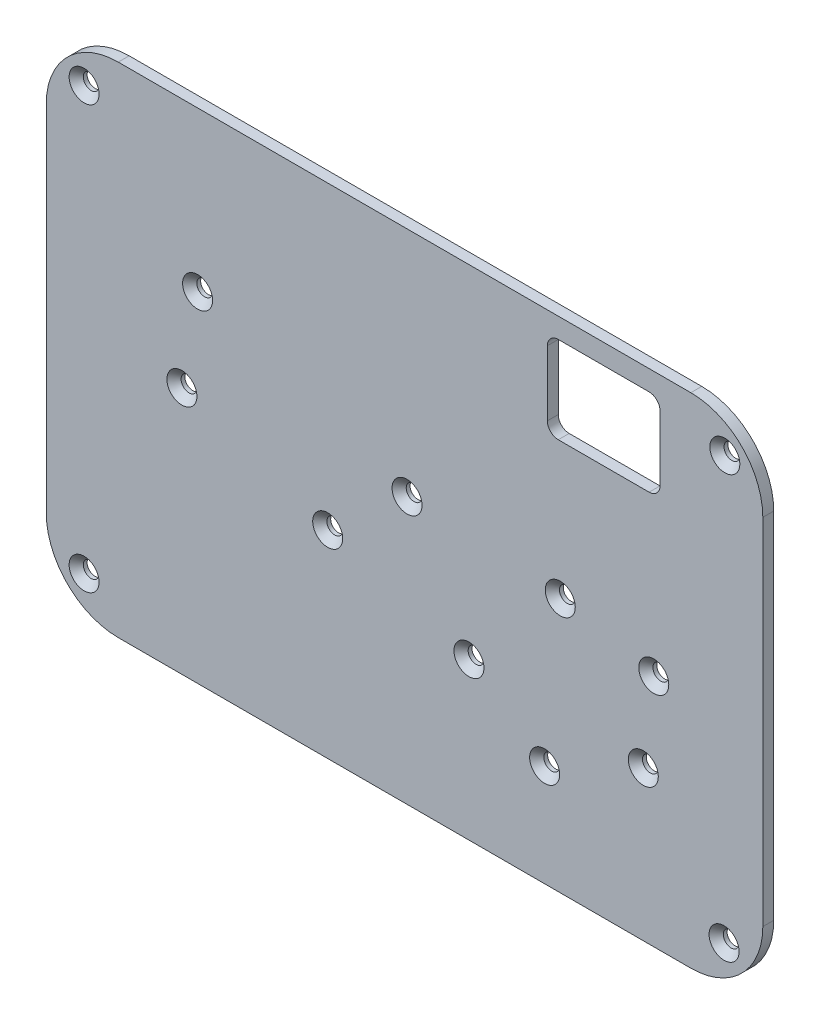
SolidWorks part; units mm, degrees
material "Легированная сталь"
ref_plane "Спереди" through (0, 0, 0) normal (0, 0, 1) x (1, 0, 0)
ref_plane "Сверху" through (0, 0, 0) normal (0, 1, 0) x (1, 0, 0)
ref_plane "Справа" through (0, 0, 0) normal (1, 0, 0) x (0, 0, -1)
sketch "Эскиз9" plane through (0, 0, 0) normal (0, 0, 1) x (1, 0, 0)
  line L0 (89.2786, -11) -> (85.3215, -11)
  line L1 (79.0604, -10) -> (0, -10)
  line L2 (-10, 0) -> (-10, 31.7451)
  line L3 (-11, 38.0208) -> (-11, 41.9792)
  line L4 (-10, 48.1396) -> (-10, 65)
  line L5 (0, 75) -> (12.025, 75)
  line L6 (12.025, 75) -> (12.025, 78.2)
  line L7 (12.025, 78.2) -> (0, 78.2)
  line L8 (-13.2, 65) -> (-13.2, 0)
  line L9 (0, -13.2) -> (105, -13.2)
  line L10 (118.2, 0) -> (118.2, 65)
  line L11 (105, 78.2) -> (30.025, 78.2)
  line L12 (30.025, 78.2) -> (30.025, 75)
  line L13 (30.025, 75) -> (105, 75)
  line L14 (115, 65) -> (115, 0)
  line L15 (105, -10) -> (95.3396, -10)
  circle A0 centre (-6.2627, 71.3457) radius 2.75
  circle A1 centre (-6.2627, -6.1474) radius 2.75
  circle A2 centre (111.0955, -6.1474) radius 2.75
  circle A3 centre (111.2331, 71.3457) radius 2.75
  arc A4 (93.9799, -9.4667) -> (95.3396, -10) centre (95.3396, -8) ccw
  arc A5 (93.9799, -9.4667) -> (92.5665, -9.5204) centre (93.3, -10.2) ccw
  arc A6 (91.5856, -10.1011) -> (92.5665, -9.5204) centre (91.0994, -8.1611) ccw
  arc A7 (91.5856, -10.1011) -> (90.4374, -10.6301) centre (92.4155, -13.4129) ccw
  arc A8 (89.2786, -11) -> (90.4374, -10.6301) centre (89.2786, -9) ccw
  arc A9 (84.1626, -10.63) -> (85.3215, -11) centre (85.3215, -9) ccw
  arc A10 (84.1626, -10.63) -> (82.8537, -10.0647) centre (82.1842, -13.4126) ccw
  arc A11 (81.8153, -9.5012) -> (82.8537, -10.0647) centre (83.2459, -8.1035) ccw
  arc A12 (81.8153, -9.5012) -> (80.4201, -9.4667) centre (81.1, -10.2) ccw
  arc A13 (79.0604, -10) -> (80.4201, -9.4667) centre (79.0604, -8) ccw
  arc A14 (-1.5835, -9.8738) -> (0, -10) centre (0, 0) ccw
  arc A15 (-3.1229, -7.1543) -> (-1.5835, -9.8738) centre (-1.2668, -7.8991) ccw
  arc A16 (-3.1229, -7.1543) -> (-7.1543, -3.1229) centre (-6, -6) ccw
  arc A17 (-9.8738, -1.5835) -> (-7.1543, -3.1229) centre (-7.8991, -1.2668) ccw
  arc A18 (-10, 0) -> (-9.8738, -1.5835) centre (0, 0) ccw
  arc A19 (-9.5149, 33.0509) -> (-10, 31.7451) centre (-8, 31.7451) ccw
  arc A20 (-9.5149, 33.0509) -> (-9.5827, 34.8219) centre (-10.5, 33.9) ccw
  arc A21 (-10.1084, 35.7395) -> (-9.5827, 34.8219) centre (-8.172, 36.2397) ccw
  arc A22 (-10.1084, 35.7395) -> (-10.6306, 36.8627) centre (-13.4142, 34.8858) ccw
  arc A23 (-11, 38.0208) -> (-10.6306, 36.8627) centre (-9, 38.0208) ccw
  arc A24 (-10.6306, 43.1373) -> (-11, 41.9792) centre (-9, 41.9792) ccw
  arc A25 (-10.6306, 43.1373) -> (-10.0831, 44.3655) centre (-13.4142, 45.1142) ccw
  arc A26 (-9.5106, 45.3756) -> (-10.0831, 44.3655) centre (-8.1318, 43.9269) ccw
  arc A27 (-9.5106, 45.3756) -> (-9.4667, 46.7799) centre (-10.2, 46.1) ccw
  arc A28 (-10, 48.1396) -> (-9.4667, 46.7799) centre (-8, 48.1396) ccw
  arc A29 (-9.8738, 66.5835) -> (-10, 65) centre (0, 65) ccw
  arc A30 (-7.1543, 68.1229) -> (-9.8738, 66.5835) centre (-7.8991, 66.2668) ccw
  arc A31 (-7.1543, 68.1229) -> (-3.1229, 72.1543) centre (-6, 71) ccw
  arc A32 (-1.5835, 74.8738) -> (-3.1229, 72.1543) centre (-1.2668, 72.8991) ccw
  arc A33 (0, 75) -> (-1.5835, 74.8738) centre (0, 65) ccw
  arc A34 (0, 78.2) -> (-13.2, 65) centre (0, 65) ccw
  arc A35 (-13.2, 0) -> (0, -13.2) centre (0, 0) ccw
  arc A36 (105, -13.2) -> (118.2, 0) centre (105, 0) ccw
  arc A37 (118.2, 65) -> (105, 78.2) centre (105, 65) ccw
  arc A38 (106.5835, 74.8738) -> (105, 75) centre (105, 65) ccw
  arc A39 (108.1229, 72.1543) -> (106.5835, 74.8738) centre (106.2668, 72.8991) ccw
  arc A40 (108.1229, 72.1543) -> (112.1543, 68.1229) centre (111, 71) ccw
  arc A41 (114.8738, 66.5835) -> (112.1543, 68.1229) centre (112.8991, 66.2668) ccw
  arc A42 (115, 65) -> (114.8738, 66.5835) centre (105, 65) ccw
  arc A43 (114.8738, -1.5835) -> (115, 0) centre (105, 0) ccw
  arc A44 (112.1543, -3.1229) -> (114.8738, -1.5835) centre (112.8991, -1.2668) ccw
  arc A45 (112.1543, -3.1229) -> (108.1229, -7.1543) centre (111, -6) ccw
  arc A46 (106.5835, -9.8738) -> (108.1229, -7.1543) centre (106.2668, -7.8991) ccw
  arc A47 (105, -10) -> (106.5835, -9.8738) centre (105, 0) ccw
sketch "Net" plane through (0, 0, 0) normal (0, 0, 1) x (1, 0, 0)
  line L0 (24.2, 33) -> (24.2, 43.5)
  line L1 (22.2, 45.5) -> (16.7, 45.5)
  line L2 (14.7, 43.5) -> (14.7, 33)
  line L3 (16.7, 31) -> (22.2, 31)
  line L4 (49.7, 24.5) -> (49.7, 35.5)
  line L5 (47.7, 37.5) -> (43.2, 37.5)
  line L6 (41.2, 35.5) -> (41.2, 24.5)
  line L7 (43.2, 22.5) -> (47.7, 22.5)
  line L8 (76.2, 28) -> (67.2, 28)
  line L9 (65.2, 26) -> (65.2, 22)
  line L10 (67.2, 20) -> (76.2, 20)
  line L11 (78.2, 22) -> (78.2, 26)
  line L12 (86.2, 32.5) -> (96.2, 32.5)
  line L13 (98.2, 34.5) -> (98.2, 35.5)
  line L14 (96.2, 37.5) -> (86.2, 37.5)
  line L15 (84.2, 35.5) -> (84.2, 34.5)
  line L16 (78.2, -9) -> (81.2, -9)
  line L17 (78.2, 0.6303) -> (78.2, -9)
  line L18 (78.2, 16) -> (78.2, 10.096)
  line L19 (69.4574, 18) -> (76.2, 18)
  line L20 (67.4574, 14.9) -> (67.4574, 16)
  line L21 (54.8273, 16.5) -> (59.2731, 16.5)
  line L22 (38.1419, 19.7) -> (47.4957, 19.7)
  line L23 (35.0419, 23) -> (35.0419, 22.8)
  line L24 (26.2, 25) -> (33.0419, 25)
  line L25 (11.5609, 29) -> (22.2, 29)
  line L26 (8.4609, 32.5) -> (8.4609, 32.1)
  line L27 (1.4933, 34.5) -> (6.4609, 34.5)
  line L28 (-8.6, 32) -> (-2.8, 32)
  line L29 (-8.6, 34) -> (-8.6, 32)
  line L30 (-2.8, 34) -> (-8.6, 34)
  line L31 (-0.8, 44) -> (-0.8, 36)
  line L32 (-8.6, 46) -> (-2.8, 46)
  line L33 (-8.6, 48) -> (-8.6, 46)
  line L34 (-2.8, 48) -> (-8.6, 48)
  line L35 (9.432, 45.5) -> (2.4724, 45.5)
  line L36 (11.432, 49.2506) -> (11.432, 47.5)
  line L37 (22.2, 47.5) -> (19.6221, 47.5)
  line L38 (37.2, 44.5) -> (27.3962, 44.5)
  line L39 (47.7, 39.5) -> (43.1161, 39.5)
  line L40 (61.2, 34.5) -> (58.0497, 34.5)
  line L41 (75.9572, 30) -> (67.0095, 30)
  line L42 (77.9572, 33.5405) -> (77.9572, 32)
  line L43 (96.2, 39.5) -> (86.2, 39.5)
  line L44 (100.2, 32.9436) -> (100.2, 35.5)
  line L45 (98.2, 17.6226) -> (98.2, 25.0883)
  line L46 (96.2, -9) -> (96.2, 9.3668)
  line L47 (93.2, -9) -> (96.2, -9)
  line L48 (93.2, 12.5) -> (93.2, -9)
  line L49 (83.2, 14.5) -> (91.2, 14.5)
  line L50 (81.2, -9) -> (81.2, 12.5)
  line L51 (93.2, 30.5) -> (82.2, 30.5)
  line L52 (80.2, 28.5) -> (80.2, 18.5)
  line L53 (82.2, 16.5) -> (93.2, 16.5)
  line L54 (95.2, 18.5) -> (95.2, 28.5)
  line L55 (61.2, 32.5) -> (53.7, 32.5)
  line L56 (51.7, 30.5) -> (51.7, 20.5)
  line L57 (53.7, 18.5) -> (61.2, 18.5)
  line L58 (63.2, 20.5) -> (63.2, 30.5)
  line L59 (39.2, 29.5) -> (39.2, 40.5)
  line L60 (37.2, 42.5) -> (28.2, 42.5)
  line L61 (26.2, 40.5) -> (26.2, 29.5)
  line L62 (28.2, 27.5) -> (37.2, 27.5)
  line L63 (12.7, 38.5) -> (12.7, 41.5)
  line L64 (10.7, 43.5) -> (3.2, 43.5)
  line L65 (1.2, 41.5) -> (1.2, 38.5)
  line L66 (3.2, 36.5) -> (10.7, 36.5)
  circle A0 centre (14.5527, 48.9918) radius 1.45
  circle A1 centre (11.6734, 32.3071) radius 1.45
  circle A2 centre (38.4079, 23.0933) radius 1.45
  circle A3 centre (64.3154, 15.511) radius 1.45
  circle A4 centre (78.1897, 5.4989) radius 1.45
  circle A5 centre (96.2825, 14.2348) radius 1.45
  circle A6 centre (98.2, 29.7798) radius 1.45
  circle A7 centre (81.0572, 33.5405) radius 1.45
  circle A8 centre (52.9595, 35.666) radius 1.45
  arc A9 (22.2, 31) -> (24.2, 33) centre (22.2, 33) ccw
  arc A10 (24.2, 43.5) -> (22.2, 45.5) centre (22.2, 43.5) ccw
  arc A11 (16.7, 45.5) -> (14.7, 43.5) centre (16.7, 43.5) ccw
  arc A12 (14.7, 33) -> (16.7, 31) centre (16.7, 33) ccw
  arc A13 (47.7, 22.5) -> (49.7, 24.5) centre (47.7, 24.5) ccw
  arc A14 (49.7, 35.5) -> (47.7, 37.5) centre (47.7, 35.5) ccw
  arc A15 (43.2, 37.5) -> (41.2, 35.5) centre (43.2, 35.5) ccw
  arc A16 (41.2, 24.5) -> (43.2, 22.5) centre (43.2, 24.5) ccw
  arc A17 (78.2, 26) -> (76.2, 28) centre (76.2, 26) ccw
  arc A18 (67.2, 28) -> (65.2, 26) centre (67.2, 26) ccw
  arc A19 (65.2, 22) -> (67.2, 20) centre (67.2, 22) ccw
  arc A20 (76.2, 20) -> (78.2, 22) centre (76.2, 22) ccw
  arc A21 (84.2, 34.5) -> (86.2, 32.5) centre (86.2, 34.5) ccw
  arc A22 (96.2, 32.5) -> (98.2, 34.5) centre (96.2, 34.5) ccw
  arc A23 (98.2, 35.5) -> (96.2, 37.5) centre (96.2, 35.5) ccw
  arc A24 (86.2, 37.5) -> (84.2, 35.5) centre (86.2, 35.5) ccw
  arc A25 (78.2, 0.6303) -> (76.9451, 2.4863) centre (76.2, 0.6303) ccw
  arc A26 (76.9451, 8.24) -> (76.9451, 2.4863) centre (78.1, 5.3632) ccw
  arc A27 (76.9451, 8.24) -> (78.2, 10.096) centre (76.2, 10.096) ccw
  arc A28 (78.2, 16) -> (76.2, 18) centre (76.2, 16) ccw
  arc A29 (69.4574, 18) -> (67.4574, 16) centre (69.4574, 16) ccw
  arc A30 (61.2669, 14.6569) -> (67.4574, 14.9) centre (64.3574, 14.9) ccw
  arc A31 (61.2669, 14.6569) -> (59.2731, 16.5) centre (59.2731, 14.5) ccw
  arc A32 (54.8273, 16.5) -> (53.0031, 15.3198) centre (54.8273, 14.5) ccw
  arc A33 (49.3373, 16.9198) -> (53.0031, 15.3198) centre (51.1788, 16.1396) ccw
  arc A34 (49.3373, 16.9198) -> (47.4957, 19.7) centre (47.4957, 17.7) ccw
  arc A35 (35.0419, 22.8) -> (38.1419, 19.7) centre (38.1419, 22.8) ccw
  arc A36 (35.0419, 23) -> (33.0419, 25) centre (33.0419, 23) ccw
  arc A37 (24.2, 27) -> (26.2, 25) centre (26.2, 27) ccw
  arc A38 (24.2, 27) -> (22.2, 29) centre (22.2, 27) ccw
  arc A39 (8.4609, 32.1) -> (11.5609, 29) centre (11.5609, 32.1) ccw
  arc A40 (8.4609, 32.5) -> (6.4609, 34.5) centre (6.4609, 32.5) ccw
  arc A41 (1.4933, 34.5) -> (-0.2461, 33.4871) centre (1.4933, 32.5) ccw
  arc A42 (-2.8, 32) -> (-0.2461, 33.4871) centre (-2.8, 34.9366) ccw
  arc A43 (-2.8, 34) -> (-0.8, 36) centre (-2.8, 36) ccw
  arc A44 (-0.8, 44) -> (-2.8, 46) centre (-2.8, 44) ccw
  arc A45 (0.1039, 46.7509) -> (-2.8, 48) centre (-2.8, 44) ccw
  arc A46 (0.1039, 46.7509) -> (2.4724, 45.5) centre (2.4724, 48.3677) ccw
  arc A47 (9.432, 45.5) -> (11.432, 47.5) centre (9.432, 47.5) ccw
  arc A48 (17.6221, 49.4992) -> (11.432, 49.2506) centre (14.532, 49.2506) ccw
  arc A49 (17.6221, 49.4992) -> (19.6221, 47.5) centre (19.6221, 49.5) ccw
  arc A50 (25.6641, 45.5) -> (22.2, 47.5) centre (22.2, 43.5) ccw
  arc A51 (25.6641, 45.5) -> (27.3962, 44.5) centre (27.3962, 46.5) ccw
  arc A52 (41.1441, 41.1667) -> (37.2, 44.5) centre (37.2, 40.5) ccw
  arc A53 (41.1441, 41.1667) -> (43.1161, 39.5) centre (43.1161, 41.5) ccw
  arc A54 (49.9808, 38.7861) -> (47.7, 39.5) centre (47.7, 35.5) ccw
  arc A55 (49.9808, 38.7861) -> (51.8634, 38.5719) centre (51.1211, 40.4291) ccw
  arc A56 (56.0749, 36.1837) -> (51.8634, 38.5719) centre (53.0139, 35.6933) ccw
  arc A57 (56.0749, 36.1837) -> (58.0497, 34.5) centre (58.0497, 36.5) ccw
  arc A58 (65.073, 31.5) -> (61.2, 34.5) centre (61.2, 30.5) ccw
  arc A59 (65.073, 31.5) -> (67.0095, 30) centre (67.0095, 32) ccw
  arc A60 (75.9572, 30) -> (77.9572, 32) centre (75.9572, 32) ccw
  arc A61 (81.0756, 36.6404) -> (77.9572, 33.5405) centre (81.0572, 33.5405) ccw
  arc A62 (81.0756, 36.6404) -> (82.7917, 37.5936) centre (81.0875, 38.6404) ccw
  arc A63 (86.2, 39.5) -> (82.7917, 37.5936) centre (86.2, 35.5) ccw
  arc A64 (100.2, 35.5) -> (96.2, 39.5) centre (96.2, 35.5) ccw
  arc A65 (100.2, 32.9436) -> (100.6314, 31.7029) centre (102.2, 32.9436) ccw
  arc A66 (99.4157, 26.9281) -> (100.6314, 31.7029) centre (98.2, 29.7798) ccw
  arc A67 (99.4157, 26.9281) -> (98.2, 25.0883) centre (100.2, 25.0883) ccw
  arc A68 (98.2, 17.6226) -> (98.7318, 16.2645) centre (100.2, 17.6226) ccw
  arc A69 (97.5161, 11.2463) -> (98.7318, 16.2645) centre (96.4561, 14.1594) ccw
  arc A70 (97.5161, 11.2463) -> (96.2, 9.3668) centre (98.2, 9.3668) ccw
  arc A71 (93.2, 12.5) -> (91.2, 14.5) centre (91.2, 12.5) ccw
  arc A72 (83.2, 14.5) -> (81.2, 12.5) centre (83.2, 12.5) ccw
  arc A73 (95.2, 28.5) -> (93.2, 30.5) centre (93.2, 28.5) ccw
  arc A74 (82.2, 30.5) -> (80.2, 28.5) centre (82.2, 28.5) ccw
  arc A75 (80.2, 18.5) -> (82.2, 16.5) centre (82.2, 18.5) ccw
  arc A76 (93.2, 16.5) -> (95.2, 18.5) centre (93.2, 18.5) ccw
  arc A77 (63.2, 30.5) -> (61.2, 32.5) centre (61.2, 30.5) ccw
  arc A78 (53.7, 32.5) -> (51.7, 30.5) centre (53.7, 30.5) ccw
  arc A79 (51.7, 20.5) -> (53.7, 18.5) centre (53.7, 20.5) ccw
  arc A80 (61.2, 18.5) -> (63.2, 20.5) centre (61.2, 20.5) ccw
  arc A81 (37.2, 27.5) -> (39.2, 29.5) centre (37.2, 29.5) ccw
  arc A82 (39.2, 40.5) -> (37.2, 42.5) centre (37.2, 40.5) ccw
  arc A83 (28.2, 42.5) -> (26.2, 40.5) centre (28.2, 40.5) ccw
  arc A84 (26.2, 29.5) -> (28.2, 27.5) centre (28.2, 29.5) ccw
  arc A85 (10.7, 36.5) -> (12.7, 38.5) centre (10.7, 38.5) ccw
  arc A86 (12.7, 41.5) -> (10.7, 43.5) centre (10.7, 41.5) ccw
  arc A87 (3.2, 43.5) -> (1.2, 41.5) centre (3.2, 41.5) ccw
  arc A88 (1.2, 38.5) -> (3.2, 36.5) centre (3.2, 38.5) ccw
sketch "Outline" plane through (0, 0, 0) normal (0, 0, 1) x (1, 0, 0)
  line L7 (12.025, 78.2) -> (0, 78.2)
  line L8 (-13.2, 65) -> (-13.2, 0)
  line L9 (0, -13.2) -> (105, -13.2)
  line L10 (118.2, 0) -> (118.2, 65)
  line L11 (105, 78.2) -> (12.025, 78.2)
  arc A34 (0, 78.2) -> (-13.2, 65) centre (0, 65) ccw
  arc A35 (-13.2, 0) -> (0, -13.2) centre (0, 0) ccw
  arc A36 (105, -13.2) -> (118.2, 0) centre (105, 0) ccw
  arc A37 (118.2, 65) -> (105, 78.2) centre (105, 65) ccw
extrude "Бобышка-Вытянуть1" add sketch "Outline" along normal blind 2
hole_wizard "Отверстие с зазором M2.51" positions "Эскиз7" profile "Эскиз8" hole size "M2.5" standard "Ansi Metric" end condition through all
sketch "Эскиз7" plane through (0, 0, 2) normal (0, 0, 1) x (1, 0, 0)
  point P0 (14.5527, 48.9918)
  point P3 (11.6734, 32.3071)
  point P6 (38.4079, 23.0933)
  point P9 (64.3154, 15.511)
  point P12 (78.1897, 5.4989)
  point P15 (96.2825, 14.2348)
  point P18 (98.2, 29.7798)
  point P21 (81.0572, 33.5405)
  point P24 (52.9595, 35.666)
  point P27 (-6.2627, 71.3457)
  point P30 (-6.2627, -6.1474)
  point P33 (111.0955, -6.1474)
  point P36 (111.2331, 71.3457)
sketch "Эскиз8" plane through (14.5527, 48.9918, 2) normal (1, 0, 0) x (0, -1, 0)
  line L0 (0, 0) -> (0, 2)
  line L1 (0, 2) -> (1.45, 2)
  line L2 (1.45, 2) -> (1.45, 1.3)
  line L3 (1.45, 1.3) -> (2.75, 0)
  line L5 (2.75, 0) -> (0, 0)
  line L6 (-1.45, 1.3) -> (-2.75, 0) construction
  line L11 (0, -6.35) -> (0, 107.95) construction
  dimension "Диаметр сквозного отверстия" = 2.9
  dimension "Глубина сквозного отверстия" = 2
  dimension "Диаметр передней зенковки" = 5.5
  dimension "Угол передней зенковки" = 90
extrude "Вырез-Вытянуть1" cut sketch "Эскиз10" along normal through all both and the other way through all
sketch "Эскиз10" plane through (0, 0, -9.9367) normal (0, 0, 1) x (1, 0, 0)
  line L1 (80.6895, 74.5) -> (97.3467, 74.5)
  line L2 (78.6895, 72.5) -> (78.6895, 60.5727)
  line L3 (80.6895, 58.5727) -> (97.3467, 58.5727)
  line L4 (99.3467, 72.5) -> (99.3467, 60.5727)
  arc A0 (78.6895, 60.5727) -> (80.6895, 58.5727) centre (80.6895, 60.5727) ccw
  arc A1 (97.3467, 58.5727) -> (99.3467, 60.5727) centre (97.3467, 60.5727) ccw
  arc A2 (97.3467, 74.5) -> (99.3467, 72.5) centre (97.3467, 72.5) cw
  arc A3 (80.6895, 74.5) -> (78.6895, 72.5) centre (80.6895, 72.5) ccw
  point P14 (78.6895, 74.5)
